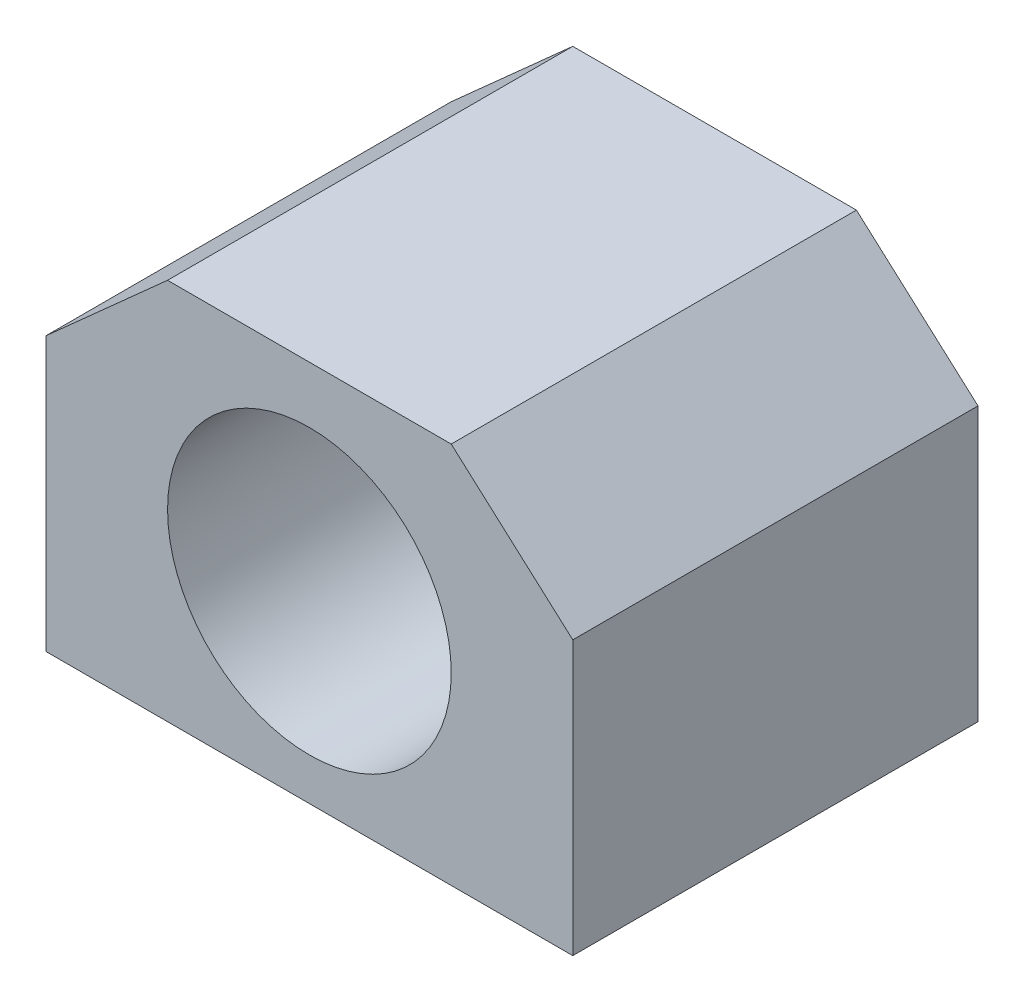
SolidWorks part; units mm, degrees
ref_plane "Front Plane" through (0, 0, 0) normal (0, 0, 1) x (1, 0, 0)
ref_plane "Top Plane" through (0, 0, 0) normal (0, 1, 0) x (1, 0, 0)
ref_plane "Right Plane" through (0, 0, 0) normal (1, 0, 0) x (0, 0, -1)
sketch "Sketch1" plane through (0, 0, 0) normal (0, 0, 1) x (1, 0, 0)
  line L0 (0, 0) -> (52, 0)
  line L1 (52, 0) -> (52, 27)
  line L5 (0, 27) -> (0, 0)
  line L6 (0, 27) -> (12, 37.7378)
  line L7 (12, 37.7378) -> (40, 37.7378)
  line L8 (40, 37.7378) -> (52, 27)
  line L9 (26, 37.7378) -> (26, 0) construction
  circle A0 centre (26, 18.1578) radius 14
  point P2 (26, 0)
  point P10 (26, 32.1578)
  point P11 (26, 18.1578)
  dimension "D1" = 52
  dimension "D2" = 28
  dimension "D3" = 5.58
  dimension "D4" = 27
  dimension "D5" = 27
  dimension "D6" = 14
extrude "Boss-Extrude1" add sketch "Sketch1" along normal blind 40
sketch "Sketch2" plane through (0, 0, 0) normal (0, -1, 0) x (1, 0, 0)
  line L0 (0, 40) -> (52, 40) construction
  line L1 (0, 40) -> (0, 0) construction
  line L2 (0, 0) -> (52, 0) construction
  line L3 (52, 40) -> (52, 0) construction
  circle A0 centre (6, 34) radius 2
  circle A1 centre (46, 34) radius 2
  circle A2 centre (6, 6) radius 2
  circle A4 centre (46, 6) radius 2
  dimension "D1" = 4
  dimension "D2" = 4
  dimension "D3" = 4
  dimension "D4" = 4
  dimension "D5" = 6
  dimension "D6" = 6
  dimension "D7" = 6
  dimension "D8" = 6
  dimension "D9" = 6
  dimension "D10" = 6
  dimension "D11" = 6
  dimension "D12" = 6
extrude "Cut-Extrude1" cut sketch "Sketch2" against normal blind 10
